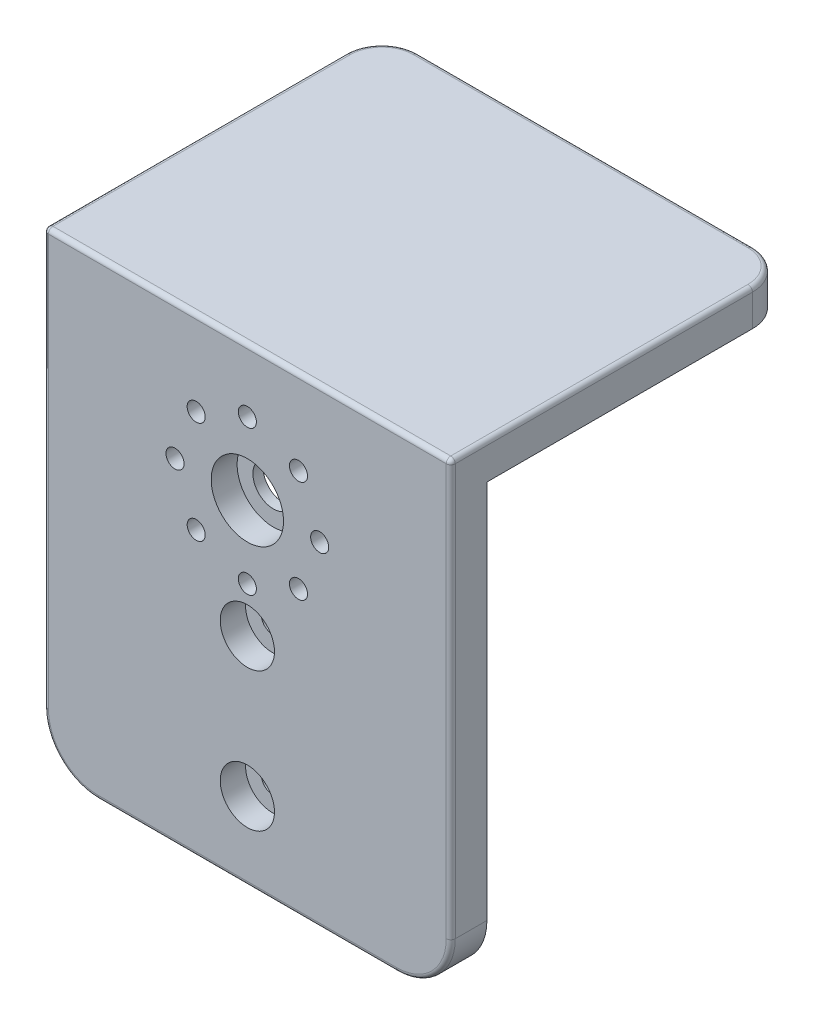
SolidWorks part; units mm, degrees
ref_plane "Front Plane" through (0, 0, 0) normal (0, 0, 1) x (1, 0, 0)
ref_plane "Top Plane" through (0, 0, 0) normal (0, 1, 0) x (1, 0, 0)
ref_plane "Right Plane" through (0, 0, 0) normal (1, 0, 0) x (0, 0, -1)
sketch "Sketch1" plane through (0, 0, 0) normal (0, 1, 0) x (1, 0, 0)
  line L1 (-22.5, -16.69) -> (22.5, -16.69)
  line L2 (-22.5, -16.69) -> (-22.5, 16.69)
  line L3 (-18.5, 20.69) -> (18.5, 20.69)
  line L4 (22.5, -16.69) -> (22.5, 16.69)
  arc A0 (-18.5, 20.69) -> (-22.5, 16.69) centre (-18.5, 16.69) ccw
  arc A1 (22.5, 16.69) -> (18.5, 20.69) centre (18.5, 16.69) ccw
  point P4 (0, -16.69)
  point P6 (22.5, 0)
  dimension "D3" = 8
  dimension "D1" = 45
  dimension "D2" = 37.38
extrude "Boss-Extrude1" add sketch "Sketch1" along normal blind 4
sketch "Sketch2" plane through (0, 0, 0) normal (0, -1, 0) x (1, 0, 0)
  line L0 (22.5, 16.69) -> (22.5, -16.69) construction
  line L1 (-22.5, 16.69) -> (22.5, 16.69)
  line L2 (-22.5, 16.69) -> (-22.5, 12.69)
  line L3 (-22.5, 12.69) -> (22.5, 12.69)
  line L4 (22.5, 16.69) -> (22.5, 12.69)
  dimension "D1" = 4
extrude "Boss-Extrude2" add sketch "Sketch2" along normal blind 48
sketch "Sketch3" plane through (0, 0, 12.69) normal (0, 0, -1) x (-1, 0, 0)
  line L0 (0, -48) -> (0, 0) construction
  line L1 (22.5, -48) -> (-22.5, -48) construction
  circle A0 centre (0, -39.35) radius 1.25
  circle A1 centre (0, -24) radius 1.25
  dimension "D1" = 2.5
  dimension "D2" = 15.35
  dimension "D3" = 24
extrude "Cut-Extrude1" cut sketch "Sketch3" against normal through all
fillet "Fillet1" radius 6 2 edges at (22.5, -48, 14.69) (-22.5, -48, 14.69)
fillet "Fillet2" radius 0.5 11 edges at (0, 4, 16.69) (22.5, 4, 0) (21.3284, 4, -19.5184) (0, 4, -20.69) (-21.3284, 4, -19.5184) (-22.5, 4, 0) (-22.5, -19, 16.69) (-20.7426, -46.2426, 16.69) (0, -48, 16.69) (20.7426, -46.2426, 16.69) (22.5, -19, 16.69)
sketch "Sketch6" plane through (0, 0, 12.69) normal (0, 0, -1) x (-1, 0, 0)
  circle A0 centre (0, -11) radius 2.255
  dimension "D1" = 4.51
  dimension "D2" = 11
extrude "Cut-Extrude2" cut sketch "Sketch6" against normal through all
sketch "Sketch7" plane through (0, 0, 12.69) normal (0, 0, -1) x (-1, 0, 0)
  circle A0 centre (0, -19) radius 1
  circle A1 centre (-5.6569, -16.6569) radius 1
  circle A2 centre (-8, -11) radius 1
  circle A3 centre (-5.6569, -5.3431) radius 1
  circle A4 centre (0, -3) radius 1
  circle A5 centre (5.6569, -5.3431) radius 1
  circle A6 centre (8, -11) radius 1
  circle A7 centre (5.6569, -16.6569) radius 1
  point P2 (0, -11)
  point P20 (0, -11)
  dimension "D1" = 2
  dimension "D2" = 8
  dimension "D3" = 8
extrude "Cut-Extrude3" cut sketch "Sketch7" against normal through all
sketch "Sketch8" plane through (0, 0, 16.69) normal (0, 0, 1) x (1, 0, 0)
  circle A0 centre (0, -11) radius 4
  dimension "D1" = 8
extrude "Cut-Extrude4" cut sketch "Sketch8" against normal blind 2.87
sketch "Sketch9" plane through (0, 0, 16.69) normal (0, 0, 1) x (1, 0, 0)
  circle A0 centre (0, -24) radius 3
  circle A1 centre (0, -39.35) radius 3
  dimension "D1" = 6
extrude "Cut-Extrude5" cut sketch "Sketch9" against normal blind 2.8
sketch "Sketch10" plane through (0, 0, 0) normal (0, -1, 0) x (1, 0, 0)
  line L0 (-16.5, 16.69) -> (16.5, 16.69) construction
  circle A0 centre (16.5, -16.17) radius 2
  circle A1 centre (16.5, -4.17) radius 1.95
  dimension "D1" = 4
  dimension "D2" = 3.9
  dimension "D3" = 12
  dimension "D4" = 16.5
  dimension "D5" = 32.86
extrude "Boss-Extrude3" add sketch "Sketch10" along normal blind 3
